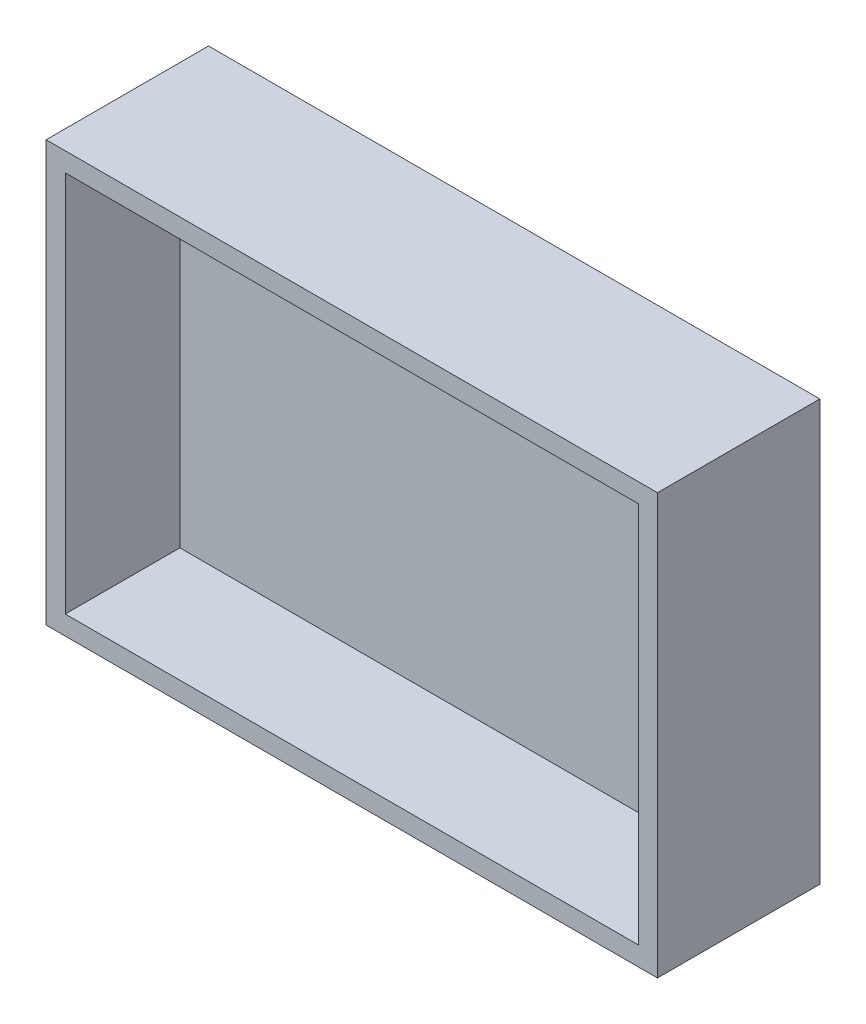
SolidWorks part; units mm, degrees
ref_plane "Alzado" through (0, 0, 0) normal (0, 0, 1) x (1, 0, 0)
ref_plane "Planta" through (0, 0, 0) normal (0, 1, 0) x (1, 0, 0)
ref_plane "Vista lateral" through (0, 0, 0) normal (1, 0, 0) x (0, 0, -1)
sketch "Croquis1" plane through (0, 0, 0) normal (0, 0, 1) x (1, 0, 0)
  line L1 (0, 0) -> (-60, 0)
  line L2 (0, 0) -> (0, 40)
  line L3 (0, 40) -> (-60, 40)
  line L4 (-60, 0) -> (-60, 40)
  line L5 (2, -2) -> (-62, -2)
  line L6 (2, -2) -> (2, 42)
  line L7 (2, 42) -> (-62, 42)
  line L8 (-62, -2) -> (-62, 42)
  dimension "D1" = 60
  dimension "D2" = 40
  dimension "D3" = 64
  dimension "D4" = 44
  dimension "D5" = 2
  dimension "D6" = 2
extrude "Saliente-Extruir1" add sketch "Croquis1" along normal blind 12
sketch "Croquis2" plane through (0, 0, 0) normal (0, 0, -1) x (-1, 0, 0)
  line L1 (-2, 42) -> (62, 42)
  line L2 (-2, 42) -> (-2, -2)
  line L3 (-2, -2) -> (62, -2)
  line L4 (62, 42) -> (62, -2)
extrude "Saliente-Extruir2" add sketch "Croquis2" along normal blind 5
